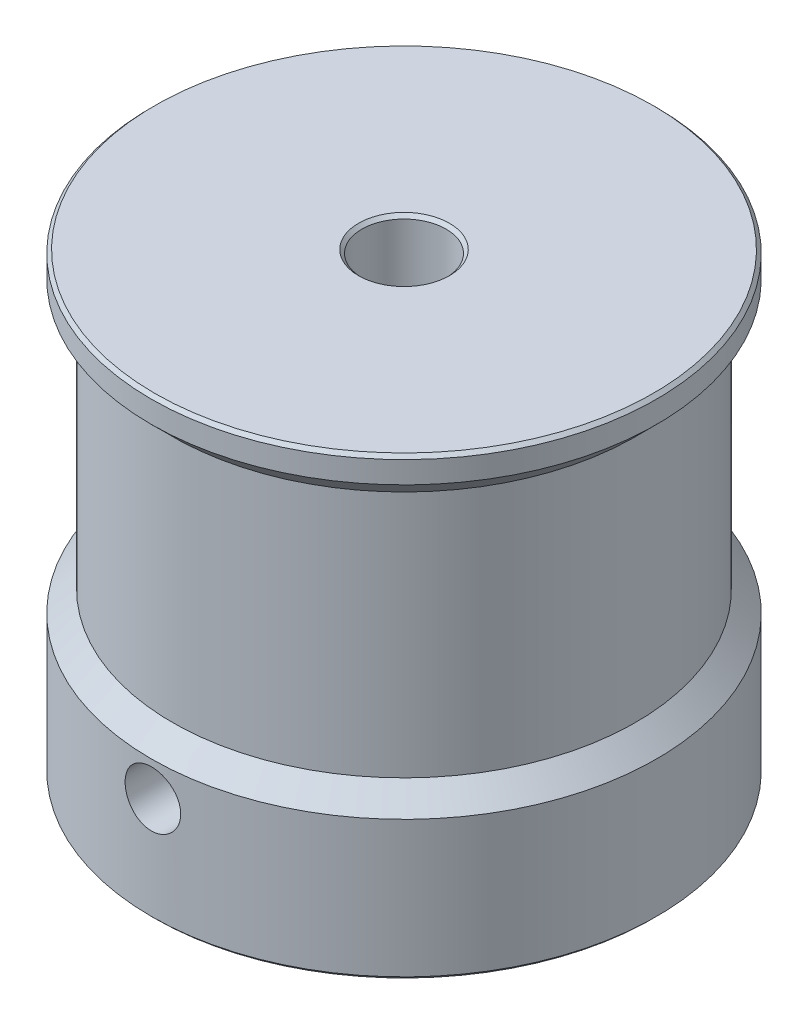
SolidWorks part; units mm, degrees
material "POM Ацеталь кополимер"
ref_plane "Спереди" through (0, 0, 0) normal (0, 0, 1) x (1, 0, 0)
ref_plane "Сверху" through (0, 0, 0) normal (0, 1, 0) x (1, 0, 0)
ref_plane "Справа" through (0, 0, 0) normal (1, 0, 0) x (0, 0, -1)
sketch "Эскиз1" plane through (0, 0, 0) normal (0, 0, 1) x (1, 0, 0)
  line L2 (13.75, 9.55) -> (13.75, 24.25)
  line L5 (15, 8.3) -> (15, 0)
  line L8 (13.75, 9.55) -> (15, 8.3)
  line L13 (15, 27) -> (2.5, 27)
  line L14 (0, 0) -> (0, 50000) construction
  line L15 (2.5, 27) -> (2.5, 2.5)
  line L17 (13.75, 24.25) -> (15, 25.5)
  line L18 (15, 25.5) -> (15, 27)
  line L19 (15, 0) -> (11.5, 0)
  line L20 (11.5, 0) -> (11.5, 2.5)
  line L21 (11.5, 2.5) -> (2.5, 2.5)
  point P9 (15, 7.3268)
  point P15 (0, 0)
  point P17 (15, 26.3883)
  point P20 (0, 0)
  dimension "D1" = 30
  dimension "D2" = 23
  dimension "D3" = 2.5
  dimension "D4" = 27.5
  dimension "D5" = 135
  dimension "D6" = 1.5
  dimension "D7" = 5
  dimension "D8" = 135
  dimension "D9" = 8.3
  dimension "D10" = 25.5
revolve "База" add sketch "Эскиз1" angle 360 about L14
hole_wizard "Фиксатор-M4" positions "Эскиз20" profile "Эскиз21" tap size "M4" standard "DIN"
sketch "Эскиз20" plane through (0, 0, 0) normal (0, 0, 1) x (1, 0, 0)
  point P0 (0, 6.25)
  point P4 (0, 3.8306)
  dimension "D1" = 6.25
sketch "Эскиз21" plane through (0, 6.25, 0) normal (1, 0, 0) x (0, 1, 0)
  line L0 (0, 0) -> (0, 15)
  line L1 (0, 15) -> (1.65, 15)
  line L2 (1.65, 15) -> (1.65, 0)
  line L5 (1.65, 0) -> (0, 0)
  line L11 (0, -6.35) -> (0, 107.95) construction
  dimension "Диаметр проходного сверла" = 3.3
  dimension "Глубина проходного сверла" = 15
cosmetic thread "Отверстие резьбы1" parameters "D1"=15, "D2"=4
chamfer "Фаска1" distance 0.2 angle 45 5 edges at (0, 2.5, -2.5) (0, 0, -15) (0, 0, -11.5) (0, 27, -2.5) (0, 27, -15)
